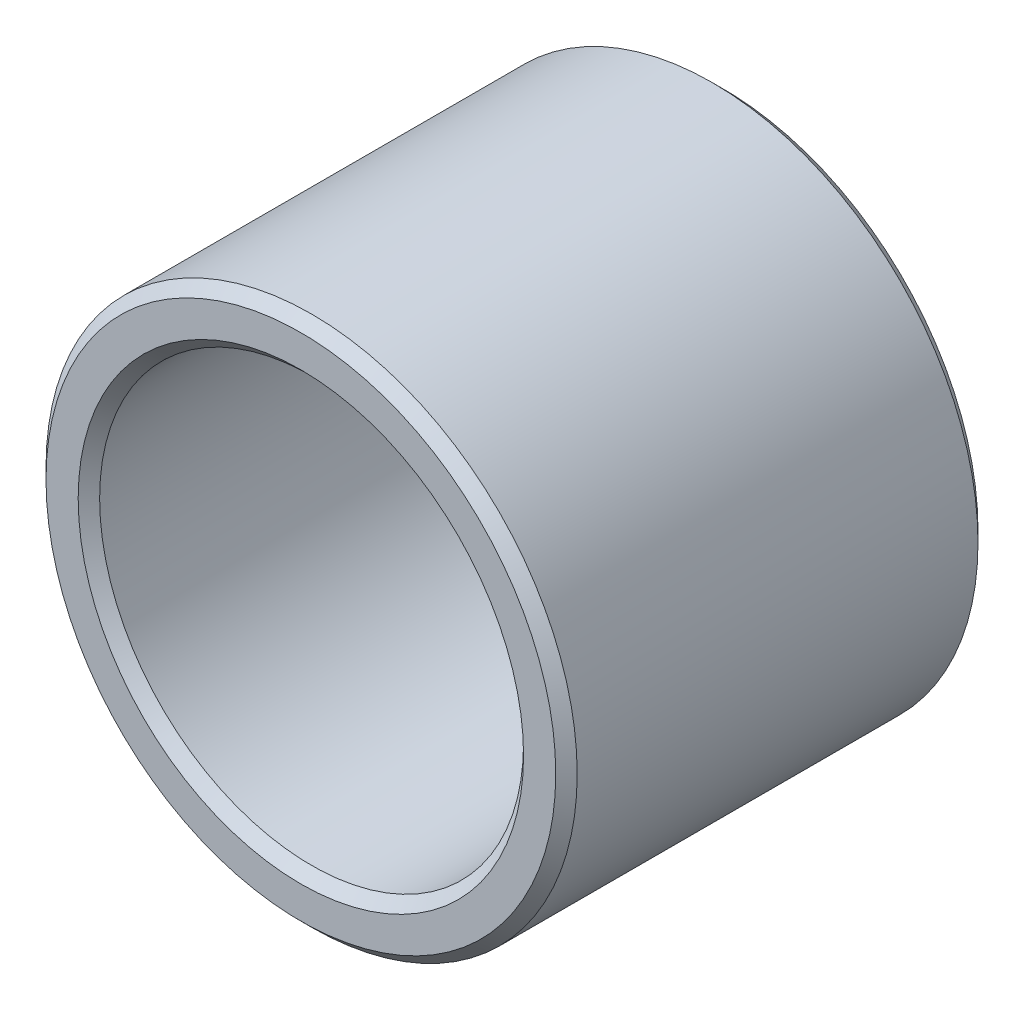
SolidWorks part; units mm, degrees
ref_plane "Front Plane" through (0, 0, 0) normal (0, 0, 1) x (1, 0, 0)
ref_plane "Top Plane" through (0, 0, 0) normal (0, 1, 0) x (1, 0, 0)
ref_plane "Right Plane" through (0, 0, 0) normal (1, 0, 0) x (0, 0, -1)
sketch "Sketch1" plane through (0, 0, 0) normal (0, 0, 1) x (1, 0, 0)
  line L0 (3.1877, 0) -> (3.9942, 0) construction
  circle A0 centre (0, 0) radius 3.1877 construction
  circle A1 centre (0, 0) radius 3.9942 construction
  circle A2 centre (0, 0) radius 3.9751 construction
  circle A3 centre (0, 0) radius 3.175 construction
  dimension "For Shaft Diameter" = 6.35
  dimension "For Housing ID" = 7.9502
  dimension "OD" = 7.9883
  dimension "ID" = 6.3754
  dimension "D3" = 0.8065
sketch "Sketch13" plane through (0, 0, 0) normal (1, 0, 0) x (0, 0, -1)
  line L0 (3.175, 0) -> (-3.175, 0) construction
  line L1 (3.175, 3.9942) -> (-3.175, 3.9942) construction
  line L2 (0, 3.9942) -> (0, -3.9942) construction
  line L3 (0, 3.9942) -> (0, -3.9942) construction
  point P4 (0, 0)
  point P8 (0, 3.9942)
  dimension "Length" = 6.35
sketch "Sketch14" plane through (0, 0, 0) normal (0, 0, 1) x (1, 0, 0)
  circle A0 centre (0, 0) radius 3.1877 construction
  circle A1 centre (0, 0) radius 3.9942 construction
  circle A2 centre (0, 0) radius 3.1877
  circle A3 centre (0, 0) radius 3.9942
extrude "Boss-Extrude1" add sketch "Sketch14" against normal up to vertex (3.175 mm away) and the other way up to vertex (3.175 mm away) up to point (0, 3.9942, -3.175) other way up to point (0, 3.9942, 3.175)
chamfer "Chamfer1" distance 0.1613 angle 45 4 edges at (3.9942, 0, -3.175) (3.1877, 0, -3.175) (3.1877, 0, 3.175) (3.9942, 0, 3.175)
equation "\"D1@Chamfer1\"=(\"OD@Sketch1\"-\"ID@Sketch1\")*.1"
